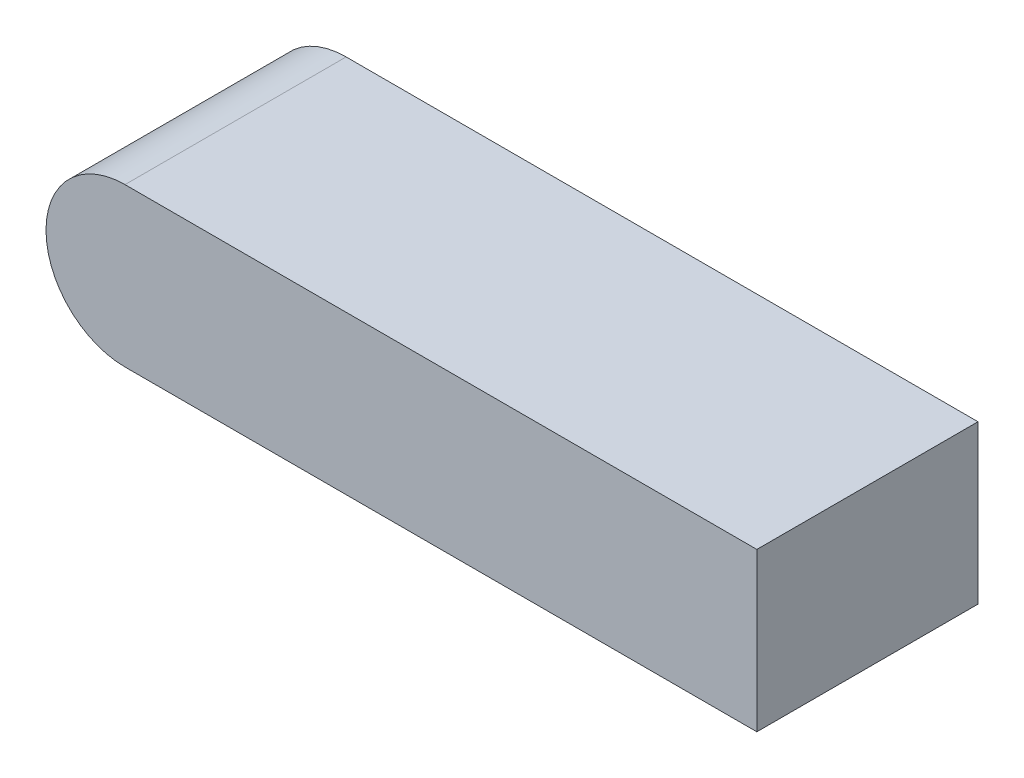
SolidWorks part; units mm, degrees
ref_plane "Front Plane" through (0, 0, 0) normal (0, 0, 1) x (1, 0, 0)
ref_plane "Top Plane" through (0, 0, 0) normal (0, 1, 0) x (1, 0, 0)
ref_plane "Right Plane" through (0, 0, 0) normal (1, 0, 0) x (0, 0, -1)
sketch "Sketch1" plane through (0, 0, 0) normal (0, 0, 1) x (1, 0, 0)
  line L1 (-50, -12.5) -> (50, -12.5)
  line L3 (-50, 12.5) -> (50, 12.5)
  line L4 (50, -12.5) -> (50, 12.5)
  line L5 (-50, -12.5) -> (50, 12.5) construction
  line L6 (-50, 12.5) -> (50, -12.5) construction
  arc A0 (-50, 12.5) -> (-50, -12.5) centre (-50, 0) ccw
  point P0 (0, 0)
  dimension "D1" = 25
  dimension "D2" = 100
extrude "Boss-Extrude1" add sketch "Sketch1" along normal blind 35
